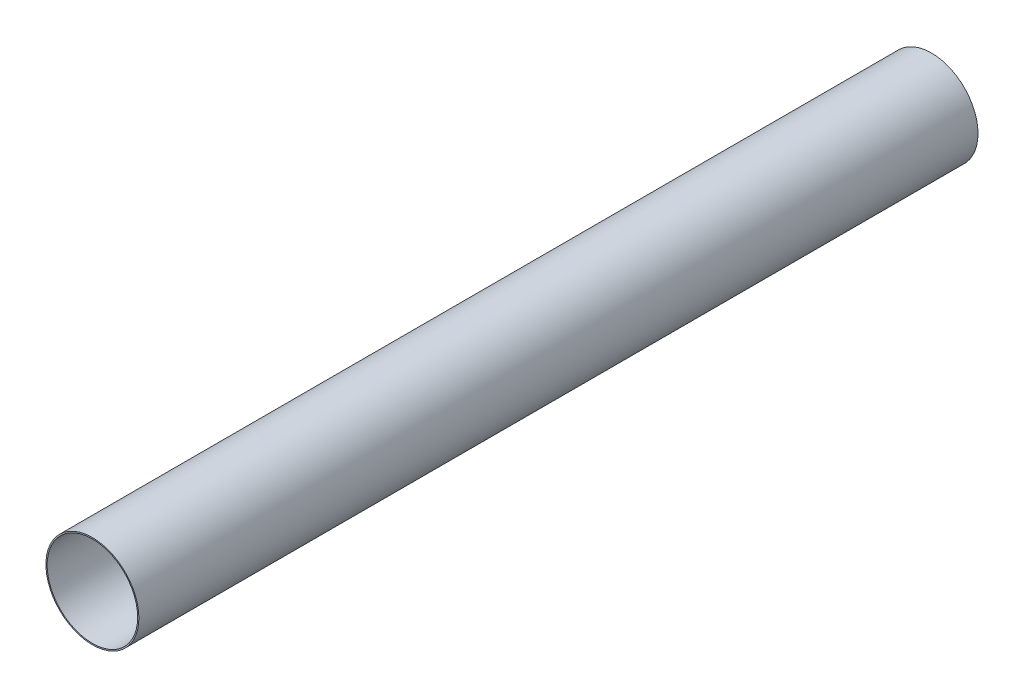
SolidWorks part; units mm, degrees
material "Acrylic (Medium-high impact)"
ref_plane "Front Plane" through (0, 0, 0) normal (0, 0, 1) x (1, 0, 0)
ref_plane "Top Plane" through (0, 0, 0) normal (0, 1, 0) x (1, 0, 0)
ref_plane "Right Plane" through (0, 0, 0) normal (1, 0, 0) x (0, 0, -1)
sketch "Sketch1" plane through (0, 0, 0) normal (0, 0, 1) x (1, 0, 0)
  circle A0 centre (0, 0) radius 21.1074
  circle A1 centre (0, 0) radius 20.5486
  dimension "D1" = 42.2148
  dimension "D2" = 0.5588
extrude "Extrude1" add sketch "Sketch1" along normal blind 381
